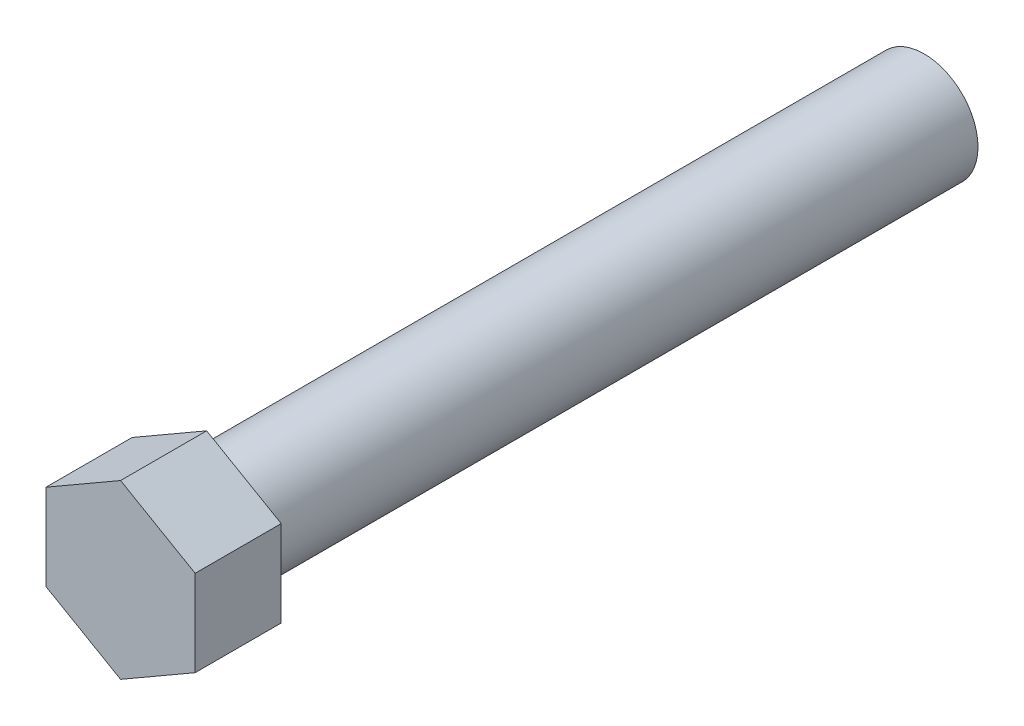
SolidWorks part; units mm, degrees
ref_plane "Front Plane" through (0, 0, 0) normal (0, 0, 1) x (1, 0, 0)
ref_plane "Top Plane" through (0, 0, 0) normal (0, 1, 0) x (1, 0, 0)
ref_plane "Right Plane" through (0, 0, 0) normal (1, 0, 0) x (0, 0, -1)
sketch "Sketch1" plane through (0, 0, 0) normal (0, 0, 1) x (1, 0, 0)
  line L0 (-109.6703, 0) -> (107.8751, 0) construction
  line L1 (0, 55.4879) -> (0, -63.8111) construction
  circle A0 centre (0, 0) radius 7.5
  dimension "D1" = 15
extrude "Boss-Extrude1" add sketch "Sketch1" along normal blind 100
sketch "Sketch2" plane through (0, 0, 100) normal (0, 0, 1) x (1, 0, 0)
  line L1 (0, -12) -> (10.3923, -6)
  line L2 (10.3923, -6) -> (10.3923, 6)
  line L3 (10.3923, 6) -> (0, 12)
  line L4 (0, 12) -> (-10.3923, 6)
  line L5 (-10.3923, 6) -> (-10.3923, -6)
  line L6 (-10.3923, -6) -> (0, -12)
  circle A0 centre (0, 0) radius 10.3923 construction
  dimension "D1" = 12
extrude "Boss-Extrude2" add sketch "Sketch2" along normal blind 12
